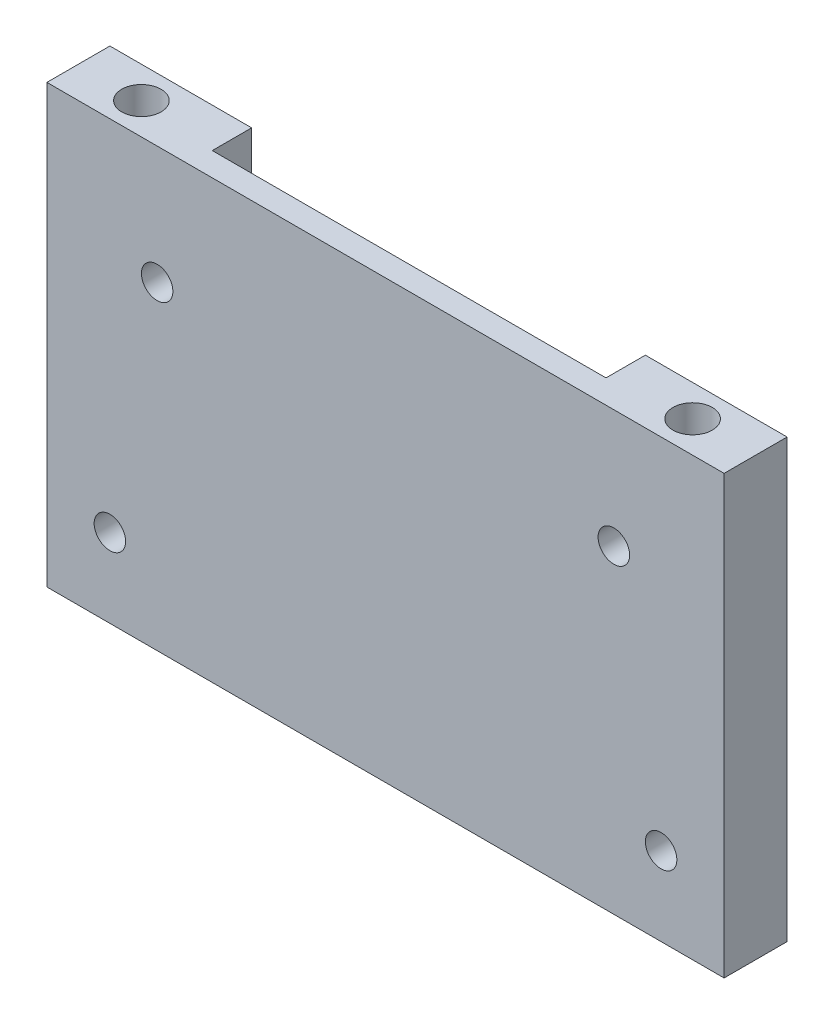
SolidWorks part; units mm, degrees
material "6061 合金"
ref_plane "前视基准面" through (0, 0, 0) normal (0, 0, 1) x (1, 0, 0)
ref_plane "上视基准面" through (0, 0, 0) normal (0, 1, 0) x (1, 0, 0)
ref_plane "右视基准面" through (0, 0, 0) normal (1, 0, 0) x (0, 0, -1)
sketch "草图1" plane through (0, 0, 0) normal (0, 0, 1) x (1, 0, 0)
  line L1 (0, 0) -> (86, 0)
  line L2 (0, 0) -> (0, 55.5)
  line L3 (0, 55.5) -> (86, 55.5)
  line L4 (86, 0) -> (86, 55.5)
  dimension "D1" = 86
  dimension "D2" = 55.5
extrude "拉伸1" add sketch "草图1" along normal blind 8
sketch "草图2" plane through (0, 55.5, 0) normal (0, 1, 0) x (-1, 0, 0)
  line L0 (-43, 8) -> (-43, -11.0481) construction
  line L1 (-86, 8) -> (0, 8) construction
  line L2 (-86, 4) -> (-65.081, 4) construction
  line L3 (-86, 8) -> (-86, 0) construction
  circle A0 centre (-78, 4) radius 2.5
  circle A1 centre (-8, 4) radius 2.5
  dimension "D1" = 5
  dimension "D2" = 5
  dimension "D3" = 70
extrude "切除-拉伸1" cut sketch "草图2" against normal blind 25
sketch "草图3" plane through (0, 0, 0) normal (0, 0, -1) x (-1, 0, 0)
  line L0 (-86, 55.5) -> (0, 55.5) construction
  line L1 (-68, 55.5) -> (-18, 55.5)
  line L2 (-68, 55.5) -> (-68, 0)
  line L3 (-68, 0) -> (-18, 0)
  line L4 (-18, 55.5) -> (-18, 0)
  line L5 (0, 0) -> (-86, 0) construction
  line L6 (-43, 44.4681) -> (-43, -7.967) construction
  dimension "D1" = 50
extrude "切除-拉伸2" cut sketch "草图3" against normal blind 5
sketch "草图4" plane through (0, 0, 0) normal (0, 0, -1) x (-1, 0, 0)
  line L0 (-72, 40.5) -> (-14, 40.5) construction
  line L1 (-78, 10) -> (-8, 10) construction
  line L2 (-43, 55.5) -> (-43, -12.0977) construction
  line L3 (-18, 55.5) -> (-68, 55.5) construction
  line L4 (-68, 0) -> (-86, 0) construction
  circle A0 centre (-72, 40.5) radius 2
  circle A1 centre (-78, 10) radius 2
  circle A2 centre (-14, 40.5) radius 2
  circle A3 centre (-8, 10) radius 2
  dimension "D5" = 4
  dimension "D1" = 58
  dimension "D2" = 70
  dimension "D3" = 15
  dimension "D4" = 10
extrude "切除-拉伸3" cut sketch "草图4" against normal through all
